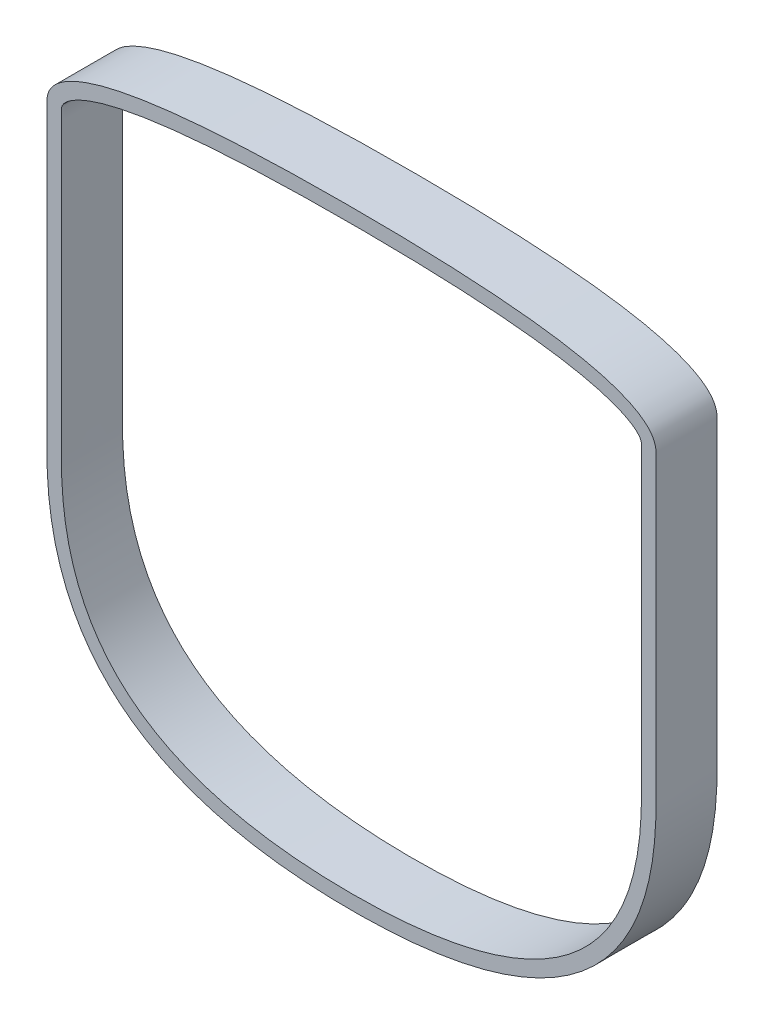
SolidWorks part; units mm, degrees
ref_plane "Front Plane" through (0, 0, 0) normal (0, 0, 1) x (1, 0, 0)
ref_plane "Top Plane" through (0, 0, 0) normal (0, 1, 0) x (1, 0, 0)
ref_plane "Right Plane" through (0, 0, 0) normal (1, 0, 0) x (0, 0, -1)
sketch "Sketch1" plane through (0, 0, 0) normal (0, 0, 1) x (1, 0, 0)
  line L0 (-99.76, 0) -> (99.76, 0) construction
  line L1 (-99.76, 0) -> (-99.76, 99.8379) construction
  line L2 (-99.76, 99.8379) -> (99.76, 99.8379) construction
  line L3 (0, 99.8379) -> (0, -99.8379) construction
  spline S0 degree 3 poles (91.3684, -59.6553) (93.1073, -56.2364) (94.4805, -52.8324) (96.7128, -45.8785) (97.5713, -42.3286) (98.5342, -36.9116) (98.8012, -35.0907) (99.1262, -32.3378) (99.2218, -31.4168) (99.3883, -29.577) (99.4592, -28.6571) (99.6375, -25.897) (99.7105, -24.0566) (99.7576, -21.2957) (99.7608, -20.3753) (99.76, -18.5345) (99.76, -17.6141) (99.76, -1.9671) (99.76, 27.4859) (99.76, 58.7798) (99.76, 75.8073) (99.76, 78.3384) (99.76, 79.0287) (99.76, 79.4889) (99.7614, 79.719) (99.7579, 80.1792) (99.7479, 80.4101) (99.7047, 80.866) (99.6729, 81.0916) (99.546, 81.761) (99.4194, 82.1974) (99.1697, 82.8382) (99.0764, 83.0493) (98.8738, 83.4592) (98.7643, 83.6592) (98.4131, 84.245) (98.1487, 84.617) (97.279, 85.6861) (96.622, 86.3124) (95.5643, 87.1674) (95.1992, 87.438) (94.4489, 87.9562) (94.0638, 88.2035) (92.8974, 88.9074) (92.1001, 89.3298) (90.4786, 90.1111) (89.654, 90.4691) (87.9852, 91.1383) (87.1406, 91.4486) (84.5822, 92.3218) (82.8403, 92.8309) (79.349, 93.7412) (77.5968, 94.1431) (74.0828, 94.8714) (72.3211, 95.1979) (67.0254, 96.0919) (63.4809, 96.5762) (56.3741, 97.4002) (52.8117, 97.7404) (45.6739, 98.3167) (42.0987, 98.5539) (34.9383, 98.9487) (31.3517, 99.1059) (20.5966, 99.4851) (13.4283, 99.6158) (-0.9057, 99.7098) (-8.0716, 99.6806) (-22.4005, 99.4337) (-29.5635, 99.2146) (-40.3048, 98.6617) (-43.8846, 98.4397) (-51.0429, 97.8961) (-54.623, 97.5739) (-61.7561, 96.7939) (-65.3114, 96.3359) (-70.6189, 95.4945) (-72.3836, 95.1877) (-75.902, 94.5066) (-77.6556, 94.1318) (-80.2744, 93.5003) (-81.1454, 93.278) (-82.8826, 92.8046) (-83.7501, 92.5531) (-86.3327, 91.7507) (-88.0273, 91.1511) (-90.5044, 90.0977) (-91.3189, 89.7198) (-92.5182, 89.0997) (-92.9142, 88.884) (-93.6966, 88.43) (-94.0842, 88.1911) (-95.219, 87.4414) (-95.9409, 86.8985) (-96.9427, 85.9833) (-97.2643, 85.6597) (-97.8671, 84.9779) (-98.146, 84.6216) (-98.6497, 83.8719) (-98.8748, 83.4781) (-99.2585, 82.6472) (-99.4113, 82.2224) (-99.6373, 81.3534) (-99.7095, 80.909) (-99.7573, 80.2278) (-99.76, 79.9981) (-99.76, 79.5402) (-99.76, 77.4798) (-99.76, 71.7564) (-99.76, 58.936) (-99.76, 33.2953) (-99.76, 7.6546) (-99.76, -12.4917) (-99.76, -17.9861) (-99.76, -20.7333) (-99.7536, -21.6488) (-99.7173, -23.4784) (-99.6887, -24.3928) (-99.4919, -28.9617) (-99.1625, -32.6083) (-98.0734, -39.8801) (-97.3147, -43.5054) (-96.0178, -48.0197) (-95.7401, -48.9238) (-95.1528, -50.7135) (-94.8428, -51.6002) (-93.8627, -54.2354) (-93.1422, -55.9588) (-90.769, -61.0239) (-88.9051, -64.2605) (-86.1792, -68.1094) (-85.6137, -68.8699) (-84.4549, -70.3544) (-83.8603, -71.0806) (-82.0316, -73.2118) (-80.7528, -74.5697) (-76.7438, -78.4611) (-73.8403, -80.8119) (-69.9444, -83.4691) (-69.153, -83.9856) (-67.5586, -84.9824) (-66.754, -85.4638) (-64.3186, -86.8601) (-62.6667, -87.7267) (-57.6345, -90.1542) (-54.1787, -91.544) (-48.8705, -93.3474) (-47.0802, -93.9013) (-43.4611, -94.9219) (-41.6414, -95.386) (-36.176, -96.6514) (-32.515, -97.3307) (-25.1648, -98.4231) (-21.4755, -98.8359) (-14.0739, -99.4453) (-10.3617, -99.6418) (-2.9175, -99.85) (0.814, -99.8651) (8.2952, -99.7242) (12.0226, -99.5636) (23.1582, -98.7659) (30.521, -97.8204) (41.429, -95.4795) (45.0421, -94.5435) (49.5216, -93.1235) (50.4148, -92.8271) (52.1874, -92.2111) (53.068, -91.8912) (55.6918, -90.8943) (57.4171, -90.1801) (62.5141, -87.8736) (65.8069, -86.1176) (69.7623, -83.5892) (70.5462, -83.066) (72.0929, -81.9872) (72.8522, -81.4341) (75.0872, -79.7328) (76.5203, -78.5431) (80.6426, -74.801) (83.1561, -72.0769) (85.988, -68.3691) (86.5389, -67.6125) (87.6094, -66.0686) (88.13, -65.2799) (89.1339, -63.6798) (89.6169, -62.8689) (90.314, -61.6367) (90.6556, -61.0167) (91.0423, -60.2865) (91.2054, -59.972) (91.3137, -59.7621) (91.3684, -59.6553) (93.1073, -56.2364) (94.4805, -52.8324) knots -0.000488 -0.000488 0 0 0.015625 0.015625 0.03125 0.03125 0.039062 0.039062 0.042969 0.042969 0.046875 0.046875 0.054687 0.054687 0.058594 0.058594 0.0625 0.0625 0.125 0.1875 0.195312 0.197266 0.198242 0.198242 0.199219 0.199219 0.200195 0.200195 0.201172 0.201172 0.203125 0.203125 0.204102 0.204102 0.205078 0.205078 0.207031 0.207031 0.210937 0.210937 0.212891 0.212891 0.214844 0.214844 0.21875 0.21875 0.222656 0.222656 0.226562 0.226562 0.234375 0.234375 0.242187 0.242187 0.25 0.25 0.265625 0.265625 0.28125 0.28125 0.296875 0.296875 0.3125 0.3125 0.34375 0.34375 0.375 0.375 0.40625 0.40625 0.421875 0.421875 0.4375 0.4375 0.453125 0.453125 0.460937 0.460937 0.46875 0.46875 0.472656 0.472656 0.476562 0.476562 0.484375 0.484375 0.488281 0.488281 0.490234 0.490234 0.492187 0.492187 0.496094 0.496094 0.498047 0.498047 0.5 0.5 0.501953 0.501953 0.503906 0.503906 0.505859 0.505859 0.506836 0.506836 0.507812 0.515625 0.53125 0.5625 0.625 0.640625 0.648437 0.648437 0.652344 0.652344 0.65625 0.65625 0.671875 0.671875 0.6875 0.6875 0.691406 0.691406 0.695312 0.695312 0.703125 0.703125 0.71875 0.71875 0.722656 0.722656 0.726562 0.726562 0.734375 0.734375 0.75 0.75 0.753906 0.753906 0.757812 0.757812 0.765625 0.765625 0.78125 0.78125 0.789062 0.789062 0.796875 0.796875 0.8125 0.8125 0.828125 0.828125 0.84375 0.84375 0.859375 0.859375 0.875 0.875 0.90625 0.90625 0.921875 0.921875 0.925781 0.925781 0.929687 0.929687 0.9375 0.9375 0.953125 0.953125 0.957031 0.957031 0.960938 0.960938 0.96875 0.96875 0.984375 0.984375 0.988281 0.988281 0.992187 0.992187 0.996094 0.996094 0.998047 0.999023 0.999512 0.999512 1 1 1.015625 1.015625 1.03125 only from (91.421, -59.5517) to (91.421, -59.5517)
  point P8 (0, 0)
  point P9 (96.1075, 101.386)
  point P10 (131.7836, 102.8422)
  point P11 (0, 0)
  point P12 (0, 0)
  dimension "D1" = 199.52
  dimension "D2" = 199.6758
extrude "Boss-Extrude1" add sketch "Sketch1" against normal mid plane 20
sketch "Sketch2" plane through (0, 0, 10) normal (0, 0, 1) x (1, 0, 0)
  spline S2 degree 3 poles (-94.416, 81.6381) (-94.57, 81.4089) (-94.6788, 81.2186) (-94.8556, 80.8182) (-94.9236, 80.6046) (-94.9796, 80.2812) (-94.9918, 80.1728) (-95.0004, 79.9545) (-95, 79.8448) (-95, 79.5161) (-95, 78.4202) (-95, 75.571) (-95, 69.4341) (-95, 57.1605) (-95, 32.6131) (-95, 8.0658) (-95, -11.2214) (-95, -16.4815) (-95, -19.1116) (-95.0024, -19.9883) (-94.9912, -21.7417) (-94.9767, -22.6183) (-94.901, -25.2483) (-94.8104, -26.9975) (-94.5415, -30.4787) (-94.3629, -32.2119) (-93.6816, -37.3869) (-93.0356, -40.8047) (-91.926, -45.0259) (-91.689, -45.8676) (-91.183, -47.5457) (-90.9137, -48.3832) (-90.057, -50.8787) (-89.4248, -52.5102) (-87.3347, -57.3026) (-85.6842, -60.362) (-83.2615, -63.9968) (-82.759, -64.7143) (-81.7171, -66.1298) (-81.1767, -66.829) (-79.5163, -68.8752) (-78.3529, -70.1776) (-74.7014, -73.9078) (-72.0512, -76.158) (-68.493, -78.7018) (-67.7691, -79.1972) (-66.2972, -80.1615) (-65.5521, -80.6287) (-63.3, -81.9818) (-61.7721, -82.8219) (-57.1176, -85.1764) (-53.9213, -86.5272) (-49.0137, -88.2882) (-47.359, -88.831) (-44.8508, -89.5841) (-44.0105, -89.825) (-42.3213, -90.2872) (-41.4726, -90.5085) (-37.2294, -91.564) (-33.8199, -92.2519) (-26.9767, -93.3783) (-23.5431, -93.8165) (-16.6563, -94.4886) (-13.2032, -94.7237) (-6.2805, -95.0222) (-2.811, -95.0871) (2.4041, -95.0718) (4.1442, -95.0481) (7.6284, -94.9604) (9.3698, -94.896) (14.5809, -94.6366) (18.0418, -94.3763) (24.9327, -93.6481) (28.3624, -93.1789) (35.1837, -91.9854) (38.5756, -91.2638) (43.6278, -89.9428) (45.3059, -89.4622) (48.6483, -88.4106) (50.3, -87.8432) (55.1916, -86.0056) (58.3686, -84.6014) (62.9777, -82.162) (64.4879, -81.293) (66.7096, -79.8967) (67.4441, -79.415) (68.8922, -78.4223) (69.6039, -77.9127) (73.0986, -75.2981) (75.6913, -72.9918) (79.2486, -69.182) (80.379, -67.8536) (81.9885, -65.77) (82.5108, -65.06) (83.5158, -63.6249) (84, -62.898) (86.3316, -59.2176) (87.9111, -56.1271) (89.5686, -52.1019) (89.8842, -51.2887) (90.4843, -49.6464) (90.7693, -48.8164) (91.5771, -46.3102) (92.0494, -44.6297) (93.2895, -39.5624) (93.8826, -36.1501) (94.6956, -29.2707) (94.9145, -25.8036) (94.9956, -21.4415) (95.0002, -20.5672) (95.0008, -18.8187) (95, -17.9445) (95, -15.3217) (95, -13.5733) (95, -8.3278) (95, 2.1631) (95, 26.6418) (95, 51.1205) (95, 70.3538) (95, 76.0363) (95, 78.2219) (95, 78.8776) (94.9998, 79.0962) (95.0002, 79.5333) (95.0034, 79.752) (94.9946, 80.1888) (94.9681, 80.4066) (94.8787, 80.7319) (94.8409, 80.8413) (94.7535, 81.0538) (94.7042, 81.1565) (94.5429, 81.4559) (94.4176, 81.6442) (94.143, 82.0053) (93.993, 82.1792) (93.5243, 82.6759) (93.1862, 82.9741) (92.4806, 83.5328) (92.1124, 83.7924) (91.3549, 84.2846) (90.9643, 84.5173) (90.1749, 84.9563) (89.7754, 85.1629) (88.5659, 85.754) (87.7448, 86.1093) (86.0832, 86.7689) (85.2423, 87.0719) (83.5454, 87.6384) (82.6895, 87.9022) (80.9659, 88.3986) (80.0971, 88.6315) (77.486, 89.2907) (75.7396, 89.6766) (72.2391, 90.3759) (70.485, 90.6884) (66.971, 91.2592) (65.2111, 91.5171) (59.9244, 92.2244) (56.3909, 92.6102) (49.3118, 93.2665) (45.7661, 93.5362) (38.6657, 93.9901) (35.1109, 94.1734) (27.9941, 94.4722) (24.4313, 94.5884) (17.3047, 94.767) (13.7414, 94.8289) (6.6148, 94.9077) (3.0515, 94.9254) (-4.0752, 94.9226) (-7.6385, 94.9008) (-18.3286, 94.7677) (-25.4574, 94.5923) (-36.1379, 94.1216) (-39.6961, 93.9308) (-46.8078, 93.4595) (-50.3624, 93.1795) (-57.4592, 92.4969) (-61.0002, 92.0965) (-66.2945, 91.3594) (-68.0565, 91.091) (-71.573, 90.4962) (-73.3258, 90.17) (-76.8137, 89.441) (-78.5493, 89.0385) (-81.1343, 88.3516) (-81.9937, 88.1081) (-83.6973, 87.5892) (-84.5422, 87.3137) (-86.2133, 86.7189) (-87.0395, 86.3997) (-88.6679, 85.705) (-89.4697, 85.3288) (-90.6447, 84.6997) (-91.0316, 84.4787) (-91.7924, 84.0067) (-92.1682, 83.7552) (-92.8946, 83.2151) (-93.2419, 82.9286) (-93.7271, 82.4619) (-93.8828, 82.3002) (-94.1048, 82.0455) (-94.1767, 81.9586) (-94.281, 81.8243) (-94.3151, 81.7789) (-94.382, 81.6867) (-94.416, 81.6381) (-94.57, 81.4089) (-94.6788, 81.2186) knots -0.000244 -0.000244 0 0 0.000977 0.000977 0.001953 0.001953 0.002441 0.002441 0.00293 0.00293 0.003906 0.007813 0.015625 0.03125 0.0625 0.125 0.140625 0.148438 0.148438 0.152344 0.152344 0.15625 0.15625 0.164063 0.164063 0.171875 0.171875 0.1875 0.1875 0.191406 0.191406 0.195313 0.195313 0.203125 0.203125 0.21875 0.21875 0.222656 0.222656 0.226563 0.226563 0.234375 0.234375 0.25 0.25 0.253906 0.253906 0.257813 0.257813 0.265625 0.265625 0.28125 0.28125 0.289063 0.289063 0.292969 0.292969 0.296875 0.296875 0.3125 0.3125 0.328125 0.328125 0.34375 0.34375 0.359375 0.359375 0.367188 0.367188 0.375 0.375 0.390625 0.390625 0.40625 0.40625 0.421875 0.421875 0.429688 0.429688 0.4375 0.4375 0.453125 0.453125 0.460938 0.460938 0.464844 0.464844 0.46875 0.46875 0.484375 0.484375 0.492188 0.492188 0.496094 0.496094 0.5 0.5 0.515625 0.515625 0.519531 0.519531 0.523438 0.523438 0.53125 0.53125 0.546875 0.546875 0.5625 0.5625 0.566406 0.566406 0.570313 0.570313 0.578125 0.578125 0.59375 0.625 0.6875 0.703125 0.710938 0.712891 0.712891 0.713867 0.713867 0.714844 0.714844 0.71582 0.71582 0.716309 0.716309 0.716797 0.716797 0.717773 0.717773 0.71875 0.71875 0.720703 0.720703 0.722656 0.722656 0.724609 0.724609 0.726563 0.726563 0.730469 0.730469 0.734375 0.734375 0.738281 0.738281 0.742188 0.742188 0.75 0.75 0.757813 0.757813 0.765625 0.765625 0.78125 0.78125 0.796875 0.796875 0.8125 0.8125 0.828125 0.828125 0.84375 0.84375 0.859375 0.859375 0.875 0.875 0.90625 0.90625 0.921875 0.921875 0.9375 0.9375 0.953125 0.953125 0.960938 0.960938 0.96875 0.96875 0.976563 0.976563 0.980469 0.980469 0.984375 0.984375 0.988281 0.988281 0.992188 0.992188 0.994141 0.994141 0.996094 0.996094 0.998047 0.998047 0.999023 0.999023 0.999512 0.999512 0.999756 0.999756 1 1 1.000977 1.000977 1.001953 only from (-94.4468, 81.5923) to (-94.4468, 81.5923)
  spline S3 degree 3 poles (-94.416, 81.6381) (-94.57, 81.4089) (-94.6788, 81.2186) (-94.8556, 80.8182) (-94.9236, 80.6046) (-94.9796, 80.2812) (-94.9918, 80.1728) (-95.0004, 79.9545) (-95, 79.8448) (-95, 79.5161) (-95, 78.4202) (-95, 75.571) (-95, 69.4341) (-95, 57.1605) (-95, 32.6131) (-95, 8.0658) (-95, -11.2214) (-95, -16.4815) (-95, -19.1116) (-95.0024, -19.9883) (-94.9912, -21.7417) (-94.9767, -22.6183) (-94.901, -25.2483) (-94.8104, -26.9975) (-94.5415, -30.4787) (-94.3629, -32.2119) (-93.6816, -37.3869) (-93.0356, -40.8047) (-91.926, -45.0259) (-91.689, -45.8676) (-91.183, -47.5457) (-90.9137, -48.3832) (-90.057, -50.8787) (-89.4248, -52.5102) (-87.3347, -57.3026) (-85.6842, -60.362) (-83.2615, -63.9968) (-82.759, -64.7143) (-81.7171, -66.1298) (-81.1767, -66.829) (-79.5163, -68.8752) (-78.3529, -70.1776) (-74.7014, -73.9078) (-72.0512, -76.158) (-68.493, -78.7018) (-67.7691, -79.1972) (-66.2972, -80.1615) (-65.5521, -80.6287) (-63.3, -81.9818) (-61.7721, -82.8219) (-57.1176, -85.1764) (-53.9213, -86.5272) (-49.0137, -88.2882) (-47.359, -88.831) (-44.8508, -89.5841) (-44.0105, -89.825) (-42.3213, -90.2872) (-41.4726, -90.5085) (-37.2294, -91.564) (-33.8199, -92.2519) (-26.9767, -93.3783) (-23.5431, -93.8165) (-16.6563, -94.4886) (-13.2032, -94.7237) (-6.2805, -95.0222) (-2.811, -95.0871) (2.4041, -95.0718) (4.1442, -95.0481) (7.6284, -94.9604) (9.3698, -94.896) (14.5809, -94.6366) (18.0418, -94.3763) (24.9327, -93.6481) (28.3624, -93.1789) (35.1837, -91.9854) (38.5756, -91.2638) (43.6278, -89.9428) (45.3059, -89.4622) (48.6483, -88.4106) (50.3, -87.8432) (55.1916, -86.0056) (58.3686, -84.6014) (62.9777, -82.162) (64.4879, -81.293) (66.7096, -79.8967) (67.4441, -79.415) (68.8922, -78.4223) (69.6039, -77.9127) (73.0986, -75.2981) (75.6913, -72.9918) (79.2486, -69.182) (80.379, -67.8536) (81.9885, -65.77) (82.5108, -65.06) (83.5158, -63.6249) (84, -62.898) (86.3316, -59.2176) (87.9111, -56.1271) (89.5686, -52.1019) (89.8842, -51.2887) (90.4843, -49.6464) (90.7693, -48.8164) (91.5771, -46.3102) (92.0494, -44.6297) (93.2895, -39.5624) (93.8826, -36.1501) (94.6956, -29.2707) (94.9145, -25.8036) (94.9956, -21.4415) (95.0002, -20.5672) (95.0008, -18.8187) (95, -17.9445) (95, -15.3217) (95, -13.5733) (95, -8.3278) (95, 2.1631) (95, 26.6418) (95, 51.1205) (95, 70.3538) (95, 76.0363) (95, 78.2219) (95, 78.8776) (94.9998, 79.0962) (95.0002, 79.5333) (95.0034, 79.752) (94.9946, 80.1888) (94.9681, 80.4066) (94.8787, 80.7319) (94.8409, 80.8413) (94.7535, 81.0538) (94.7042, 81.1565) (94.5429, 81.4559) (94.4176, 81.6442) (94.143, 82.0053) (93.993, 82.1792) (93.5243, 82.6759) (93.1862, 82.9741) (92.4806, 83.5328) (92.1124, 83.7924) (91.3549, 84.2846) (90.9643, 84.5173) (90.1749, 84.9563) (89.7754, 85.1629) (88.5659, 85.754) (87.7448, 86.1093) (86.0832, 86.7689) (85.2423, 87.0719) (83.5454, 87.6384) (82.6895, 87.9022) (80.9659, 88.3986) (80.0971, 88.6315) (77.486, 89.2907) (75.7396, 89.6766) (72.2391, 90.3759) (70.485, 90.6884) (66.971, 91.2592) (65.2111, 91.5171) (59.9244, 92.2244) (56.3909, 92.6102) (49.3118, 93.2665) (45.7661, 93.5362) (38.6657, 93.9901) (35.1109, 94.1734) (27.9941, 94.4722) (24.4313, 94.5884) (17.3047, 94.767) (13.7414, 94.8289) (6.6148, 94.9077) (3.0515, 94.9254) (-4.0752, 94.9226) (-7.6385, 94.9008) (-18.3286, 94.7677) (-25.4574, 94.5923) (-36.1379, 94.1216) (-39.6961, 93.9308) (-46.8078, 93.4595) (-50.3624, 93.1795) (-57.4592, 92.4969) (-61.0002, 92.0965) (-66.2945, 91.3594) (-68.0565, 91.091) (-71.573, 90.4962) (-73.3258, 90.17) (-76.8137, 89.441) (-78.5493, 89.0385) (-81.1343, 88.3516) (-81.9937, 88.1081) (-83.6973, 87.5892) (-84.5422, 87.3137) (-86.2133, 86.7189) (-87.0395, 86.3997) (-88.6679, 85.705) (-89.4697, 85.3288) (-90.6447, 84.6997) (-91.0316, 84.4787) (-91.7924, 84.0067) (-92.1682, 83.7552) (-92.8946, 83.2151) (-93.2419, 82.9286) (-93.7271, 82.4619) (-93.8828, 82.3002) (-94.1048, 82.0455) (-94.1767, 81.9586) (-94.281, 81.8243) (-94.3151, 81.7789) (-94.382, 81.6867) (-94.416, 81.6381) (-94.57, 81.4089) (-94.6788, 81.2186) knots -0.000244 -0.000244 0 0 0.000977 0.000977 0.001953 0.001953 0.002441 0.002441 0.00293 0.00293 0.003906 0.007813 0.015625 0.03125 0.0625 0.125 0.140625 0.148438 0.148438 0.152344 0.152344 0.15625 0.15625 0.164063 0.164063 0.171875 0.171875 0.1875 0.1875 0.191406 0.191406 0.195313 0.195313 0.203125 0.203125 0.21875 0.21875 0.222656 0.222656 0.226563 0.226563 0.234375 0.234375 0.25 0.25 0.253906 0.253906 0.257813 0.257813 0.265625 0.265625 0.28125 0.28125 0.289063 0.289063 0.292969 0.292969 0.296875 0.296875 0.3125 0.3125 0.328125 0.328125 0.34375 0.34375 0.359375 0.359375 0.367188 0.367188 0.375 0.375 0.390625 0.390625 0.40625 0.40625 0.421875 0.421875 0.429688 0.429688 0.4375 0.4375 0.453125 0.453125 0.460938 0.460938 0.464844 0.464844 0.46875 0.46875 0.484375 0.484375 0.492188 0.492188 0.496094 0.496094 0.5 0.5 0.515625 0.515625 0.519531 0.519531 0.523438 0.523438 0.53125 0.53125 0.546875 0.546875 0.5625 0.5625 0.566406 0.566406 0.570313 0.570313 0.578125 0.578125 0.59375 0.625 0.6875 0.703125 0.710938 0.712891 0.712891 0.713867 0.713867 0.714844 0.714844 0.71582 0.71582 0.716309 0.716309 0.716797 0.716797 0.717773 0.717773 0.71875 0.71875 0.720703 0.720703 0.722656 0.722656 0.724609 0.724609 0.726563 0.726563 0.730469 0.730469 0.734375 0.734375 0.738281 0.738281 0.742188 0.742188 0.75 0.75 0.757813 0.757813 0.765625 0.765625 0.78125 0.78125 0.796875 0.796875 0.8125 0.8125 0.828125 0.828125 0.84375 0.84375 0.859375 0.859375 0.875 0.875 0.90625 0.90625 0.921875 0.921875 0.9375 0.9375 0.953125 0.953125 0.960938 0.960938 0.96875 0.96875 0.976563 0.976563 0.980469 0.980469 0.984375 0.984375 0.988281 0.988281 0.992188 0.992188 0.994141 0.994141 0.996094 0.996094 0.998047 0.998047 0.999023 0.999023 0.999512 0.999512 0.999756 0.999756 1 1 1.000977 1.000977 1.001953 only from (-94.4468, 81.5923) to (-94.4468, 81.5923)
  dimension "D1" = 4.76
extrude "Cut-Extrude1" cut sketch "Sketch2" against normal blind 20
